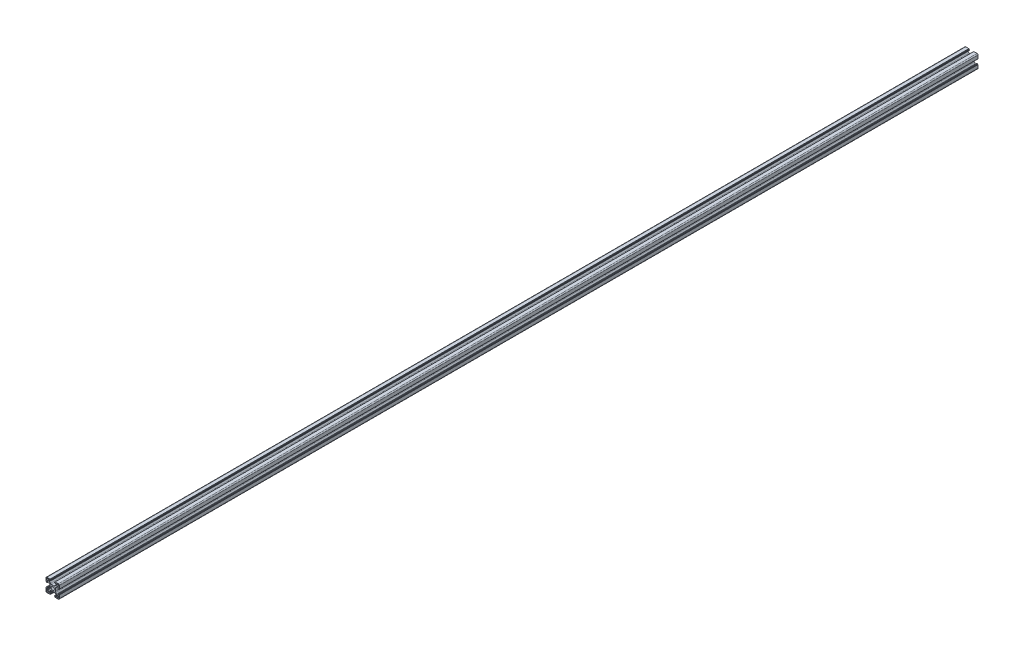
SolidWorks part; units mm, degrees
ref_plane "Спереди" through (0, 0, 0) normal (0, 0, 1) x (1, 0, 0)
ref_plane "Сверху" through (0, 0, 0) normal (0, 1, 0) x (1, 0, 0)
ref_plane "Справа" through (0, 0, 0) normal (1, 0, 0) x (0, 0, -1)
sketch "Эскиз1" plane through (0, 0, 0) normal (0, 0, 1) x (1, 0, 0)
  line L0 (-25.8933, 69.2728) -> (-28.8933, 66.2728) construction
  line L1 (-34.9933, 64.1728) -> (-33.0945, 64.1728)
  line L2 (-34.9933, 60.1728) -> (-24.9933, 70.1728) construction
  line L3 (-27.3933, 67.7728) -> (-28.8933, 69.2728) construction
  line L4 (-31.6803, 64.7586) -> (-30.3791, 66.0598)
  line L5 (-28.0933, 66.2728) -> (-26.6933, 66.2728)
  line L6 (-28.8933, 67.0728) -> (-28.8933, 68.4728)
  line L7 (-26.6933, 69.2728) -> (-28.0933, 69.2728)
  line L8 (-29.7933, 68.3728) -> (-29.7933, 67.474)
  line L9 (-31.2301, 68.246) -> (-30.7498, 68.7264)
  line L10 (-31.7933, 69.7219) -> (-31.2933, 69.7219)
  line L11 (-31.4069, 68.1728) -> (-31.6933, 68.1728)
  line L12 (-30.3962, 68.8728) -> (-30.2933, 68.8728)
  line L13 (-31.2933, 70.0228) -> (-31.2933, 69.7219)
  line L14 (-31.9433, 69.5719) -> (-31.9433, 68.4228)
  line L15 (-26.4933, 70.1728) -> (-31.1433, 70.1728)
  line L16 (-25.8933, 68.4728) -> (-25.8933, 67.0728)
  line L17 (-24.9933, 68.6728) -> (-24.9933, 64.0228)
  line L18 (-25.5943, 63.2228) -> (-26.7433, 63.2228)
  line L19 (-25.1433, 63.8728) -> (-25.4443, 63.8728)
  line L20 (-26.2933, 64.7699) -> (-26.2933, 64.8728)
  line L21 (-26.9933, 63.7592) -> (-26.9933, 63.4728)
  line L22 (-25.4443, 63.3728) -> (-25.4443, 63.8728)
  line L23 (-26.9201, 63.936) -> (-26.4398, 64.4164)
  line L24 (-26.7933, 65.3728) -> (-27.6921, 65.3728)
  line L25 (-30.4075, 63.4858) -> (-29.1063, 64.787)
  line L26 (-30.9933, 60.1728) -> (-30.9933, 62.0716)
  line L27 (-30.9933, 60.1728) -> (-30.9933, 58.274)
  line L28 (-30.4075, 56.8598) -> (-29.1063, 55.5586)
  line L29 (-28.8933, 53.2728) -> (-28.8933, 51.8728)
  line L30 (-28.0933, 54.0728) -> (-26.6933, 54.0728)
  line L31 (-25.8933, 51.8728) -> (-25.8933, 53.2728)
  line L32 (-26.7933, 54.9728) -> (-27.6921, 54.9728)
  line L33 (-26.9201, 56.4096) -> (-26.4398, 55.9292)
  line L34 (-25.4443, 56.9728) -> (-25.4443, 56.4728)
  line L35 (-26.9933, 56.5864) -> (-26.9933, 56.8728)
  line L36 (-26.2933, 55.5757) -> (-26.2933, 55.4728)
  line L37 (-25.1433, 56.4728) -> (-25.4443, 56.4728)
  line L38 (-25.5943, 57.1228) -> (-26.7433, 57.1228)
  line L39 (-24.9933, 51.6728) -> (-24.9933, 56.3228)
  line L40 (-26.6933, 51.0728) -> (-28.0933, 51.0728)
  line L41 (-26.4933, 50.1728) -> (-31.1433, 50.1728)
  line L42 (-31.9433, 50.7737) -> (-31.9433, 51.9228)
  line L43 (-31.2933, 50.3228) -> (-31.2933, 50.6237)
  line L44 (-30.3962, 51.4728) -> (-30.2933, 51.4728)
  line L45 (-31.4069, 52.1728) -> (-31.6933, 52.1728)
  line L46 (-31.7933, 50.6237) -> (-31.2933, 50.6237)
  line L47 (-31.2301, 52.0996) -> (-30.7498, 51.6192)
  line L48 (-29.7933, 51.9728) -> (-29.7933, 52.8716)
  line L49 (-31.6803, 55.587) -> (-30.3791, 54.2858)
  line L50 (-34.9933, 56.1728) -> (-33.0945, 56.1728)
  line L51 (-25.8933, 51.0728) -> (-28.8933, 54.0728) construction
  line L52 (-34.9933, 60.1728) -> (-24.9933, 50.1728) construction
  line L53 (-27.3933, 52.5728) -> (-25.8933, 54.0728) construction
  line L54 (-34.9933, 56.1728) -> (-36.8921, 56.1728)
  line L55 (-38.3063, 55.587) -> (-39.6075, 54.2858)
  line L56 (-41.8933, 54.0728) -> (-43.2933, 54.0728)
  line L57 (-41.0933, 53.2728) -> (-41.0933, 51.8728)
  line L58 (-43.2933, 51.0728) -> (-41.8933, 51.0728)
  line L59 (-40.1933, 51.9728) -> (-40.1933, 52.8716)
  line L60 (-38.7565, 52.0996) -> (-39.2369, 51.6192)
  line L61 (-38.1933, 50.6237) -> (-38.6933, 50.6237)
  line L62 (-38.5798, 52.1728) -> (-38.2933, 52.1728)
  line L63 (-39.5904, 51.4728) -> (-39.6933, 51.4728)
  line L64 (-38.6933, 50.3228) -> (-38.6933, 50.6237)
  line L65 (-38.0433, 50.7737) -> (-38.0433, 51.9228)
  line L66 (-43.4933, 50.1728) -> (-38.8433, 50.1728)
  line L67 (-44.0933, 51.8728) -> (-44.0933, 53.2728)
  line L68 (-44.9933, 51.6728) -> (-44.9933, 56.3228)
  line L69 (-44.3924, 57.1228) -> (-43.2433, 57.1228)
  line L70 (-44.8433, 56.4728) -> (-44.5424, 56.4728)
  line L71 (-43.6933, 55.5757) -> (-43.6933, 55.4728)
  line L72 (-42.9933, 56.5864) -> (-42.9933, 56.8728)
  line L73 (-44.5424, 56.9728) -> (-44.5424, 56.4728)
  line L74 (-43.0665, 56.4096) -> (-43.5469, 55.9292)
  line L75 (-43.1933, 54.9728) -> (-42.2945, 54.9728)
  line L76 (-39.5791, 56.8598) -> (-40.8803, 55.5586)
  line L77 (-38.9933, 60.1728) -> (-38.9933, 58.274)
  line L78 (-44.0933, 51.0728) -> (-41.0933, 54.0728) construction
  line L79 (-34.9933, 60.1728) -> (-44.9933, 50.1728) construction
  line L80 (-42.5933, 52.5728) -> (-41.0933, 51.0728) construction
  line L81 (-38.9933, 60.1728) -> (-38.9933, 62.0716)
  line L82 (-39.5791, 63.4858) -> (-40.8803, 64.787)
  line L83 (-41.0933, 67.0728) -> (-41.0933, 68.4728)
  line L84 (-41.8933, 66.2728) -> (-43.2933, 66.2728)
  line L85 (-44.0933, 68.4728) -> (-44.0933, 67.0728)
  line L86 (-43.1933, 65.3728) -> (-42.2945, 65.3728)
  line L87 (-43.0665, 63.936) -> (-43.5469, 64.4164)
  line L88 (-44.5424, 63.3728) -> (-44.5424, 63.8728)
  line L89 (-42.9933, 63.7592) -> (-42.9933, 63.4728)
  line L90 (-43.6933, 64.7699) -> (-43.6933, 64.8728)
  line L91 (-44.8433, 63.8728) -> (-44.5424, 63.8728)
  line L92 (-44.3924, 63.2228) -> (-43.2433, 63.2228)
  line L93 (-44.9933, 68.6728) -> (-44.9933, 64.0228)
  line L94 (-43.2933, 69.2728) -> (-41.8933, 69.2728)
  line L95 (-43.4933, 70.1728) -> (-38.8433, 70.1728)
  line L96 (-38.0433, 69.5719) -> (-38.0433, 68.4228)
  line L97 (-38.6933, 70.0228) -> (-38.6933, 69.7219)
  line L98 (-39.5904, 68.8728) -> (-39.6933, 68.8728)
  line L99 (-38.5798, 68.1728) -> (-38.2933, 68.1728)
  line L100 (-38.1933, 69.7219) -> (-38.6933, 69.7219)
  line L101 (-38.7565, 68.246) -> (-39.2369, 68.7264)
  line L102 (-40.1933, 68.3728) -> (-40.1933, 67.474)
  line L103 (-38.3063, 64.7586) -> (-39.6075, 66.0598)
  line L104 (-34.9933, 64.1728) -> (-36.8921, 64.1728)
  line L105 (-46.7574, 60.1728) -> (-23.489, 60.1728) construction
  line L106 (-44.0933, 69.2728) -> (-41.0933, 66.2728) construction
  line L107 (-34.9933, 48.0864) -> (-34.9933, 70.8917) construction
  line L108 (-34.9933, 60.1728) -> (-44.9933, 70.1728) construction
  line L109 (-42.5933, 67.7728) -> (-44.0933, 66.2728) construction
  arc A0 (-25.8933, 68.4728) -> (-26.6933, 69.2728) centre (-26.6933, 68.4728) ccw
  arc A1 (-28.0933, 69.2728) -> (-28.8933, 68.4728) centre (-28.0933, 68.4728) ccw
  arc A2 (-28.0933, 66.2728) -> (-28.8933, 67.0728) centre (-28.0933, 67.0728) cw
  arc A3 (-26.4933, 70.1728) -> (-24.9933, 68.6728) centre (-26.4933, 68.6728) cw
  arc A4 (-31.7933, 69.7219) -> (-31.9433, 69.5719) centre (-31.7933, 69.5719) ccw
  arc A5 (-31.1433, 70.1728) -> (-31.2933, 70.0228) centre (-31.1433, 70.0228) ccw
  arc A6 (-31.4069, 68.1728) -> (-31.2301, 68.246) centre (-31.4069, 68.4228) ccw
  arc A7 (-31.6933, 68.1728) -> (-31.9433, 68.4228) centre (-31.6933, 68.4228) cw
  arc A8 (-30.7498, 68.7264) -> (-30.3962, 68.8728) centre (-30.3962, 68.3728) cw
  arc A9 (-30.2933, 68.8728) -> (-29.7933, 68.3728) centre (-30.2933, 68.3728) cw
  arc A10 (-32.4933, 60.1728) -> (-34.9933, 62.6728) centre (-34.9933, 60.1728) ccw
  arc A11 (-33.0945, 64.1728) -> (-31.6803, 64.7586) centre (-33.0945, 66.1728) ccw
  arc A12 (-29.7933, 67.474) -> (-30.3791, 66.0598) centre (-31.7933, 67.474) cw
  arc A13 (-25.8933, 67.0728) -> (-26.6933, 66.2728) centre (-26.6933, 67.0728) cw
  arc A14 (-26.2933, 64.8728) -> (-26.7933, 65.3728) centre (-26.7933, 64.8728) ccw
  arc A15 (-26.4398, 64.4164) -> (-26.2933, 64.7699) centre (-26.7933, 64.7699) ccw
  arc A16 (-26.9933, 63.4728) -> (-26.7433, 63.2228) centre (-26.7433, 63.4728) ccw
  arc A17 (-26.9933, 63.7592) -> (-26.9201, 63.936) centre (-26.7433, 63.7592) cw
  arc A18 (-24.9933, 64.0228) -> (-25.1433, 63.8728) centre (-25.1433, 64.0228) cw
  arc A19 (-25.4443, 63.3728) -> (-25.5943, 63.2228) centre (-25.5943, 63.3728) cw
  arc A20 (-27.6921, 65.3728) -> (-29.1063, 64.787) centre (-27.6921, 63.3728) ccw
  arc A21 (-30.9933, 62.0716) -> (-30.4075, 63.4858) centre (-28.9933, 62.0716) cw
  arc A22 (-26.6933, 51.0728) -> (-25.8933, 51.8728) centre (-26.6933, 51.8728) ccw
  arc A23 (-25.8933, 53.2728) -> (-26.6933, 54.0728) centre (-26.6933, 53.2728) ccw
  arc A24 (-28.8933, 53.2728) -> (-28.0933, 54.0728) centre (-28.0933, 53.2728) cw
  arc A25 (-24.9933, 51.6728) -> (-26.4933, 50.1728) centre (-26.4933, 51.6728) cw
  arc A26 (-25.4443, 56.9728) -> (-25.5943, 57.1228) centre (-25.5943, 56.9728) ccw
  arc A27 (-24.9933, 56.3228) -> (-25.1433, 56.4728) centre (-25.1433, 56.3228) ccw
  arc A28 (-26.9933, 56.5864) -> (-26.9201, 56.4096) centre (-26.7433, 56.5864) ccw
  arc A29 (-26.9933, 56.8728) -> (-26.7433, 57.1228) centre (-26.7433, 56.8728) cw
  arc A30 (-26.4398, 55.9292) -> (-26.2933, 55.5757) centre (-26.7933, 55.5757) cw
  arc A31 (-26.2933, 55.4728) -> (-26.7933, 54.9728) centre (-26.7933, 55.4728) cw
  arc A32 (-34.9933, 57.6728) -> (-32.4933, 60.1728) centre (-34.9933, 60.1728) ccw
  arc A33 (-30.9933, 58.274) -> (-30.4075, 56.8598) centre (-28.9933, 58.274) ccw
  arc A34 (-27.6921, 54.9728) -> (-29.1063, 55.5586) centre (-27.6921, 56.9728) cw
  arc A35 (-28.0933, 51.0728) -> (-28.8933, 51.8728) centre (-28.0933, 51.8728) cw
  arc A36 (-30.2933, 51.4728) -> (-29.7933, 51.9728) centre (-30.2933, 51.9728) ccw
  arc A37 (-30.7498, 51.6192) -> (-30.3962, 51.4728) centre (-30.3962, 51.9728) ccw
  arc A38 (-31.6933, 52.1728) -> (-31.9433, 51.9228) centre (-31.6933, 51.9228) ccw
  arc A39 (-31.4069, 52.1728) -> (-31.2301, 52.0996) centre (-31.4069, 51.9228) cw
  arc A40 (-31.1433, 50.1728) -> (-31.2933, 50.3228) centre (-31.1433, 50.3228) cw
  arc A41 (-31.7933, 50.6237) -> (-31.9433, 50.7737) centre (-31.7933, 50.7737) cw
  arc A42 (-29.7933, 52.8716) -> (-30.3791, 54.2858) centre (-31.7933, 52.8716) ccw
  arc A43 (-33.0945, 56.1728) -> (-31.6803, 55.587) centre (-33.0945, 54.1728) cw
  arc A44 (-44.0933, 51.8728) -> (-43.2933, 51.0728) centre (-43.2933, 51.8728) ccw
  arc A45 (-41.8933, 51.0728) -> (-41.0933, 51.8728) centre (-41.8933, 51.8728) ccw
  arc A46 (-41.8933, 54.0728) -> (-41.0933, 53.2728) centre (-41.8933, 53.2728) cw
  arc A47 (-43.4933, 50.1728) -> (-44.9933, 51.6728) centre (-43.4933, 51.6728) cw
  arc A48 (-38.1933, 50.6237) -> (-38.0433, 50.7737) centre (-38.1933, 50.7737) ccw
  arc A49 (-38.8433, 50.1728) -> (-38.6933, 50.3228) centre (-38.8433, 50.3228) ccw
  arc A50 (-38.5798, 52.1728) -> (-38.7565, 52.0996) centre (-38.5798, 51.9228) ccw
  arc A51 (-38.2933, 52.1728) -> (-38.0433, 51.9228) centre (-38.2933, 51.9228) cw
  arc A52 (-39.2369, 51.6192) -> (-39.5904, 51.4728) centre (-39.5904, 51.9728) cw
  arc A53 (-39.6933, 51.4728) -> (-40.1933, 51.9728) centre (-39.6933, 51.9728) cw
  arc A54 (-37.4933, 60.1728) -> (-34.9933, 57.6728) centre (-34.9933, 60.1728) ccw
  arc A55 (-36.8921, 56.1728) -> (-38.3063, 55.587) centre (-36.8921, 54.1728) ccw
  arc A56 (-40.1933, 52.8716) -> (-39.6075, 54.2858) centre (-38.1933, 52.8716) cw
  arc A57 (-44.0933, 53.2728) -> (-43.2933, 54.0728) centre (-43.2933, 53.2728) cw
  arc A58 (-43.6933, 55.4728) -> (-43.1933, 54.9728) centre (-43.1933, 55.4728) ccw
  arc A59 (-43.5469, 55.9292) -> (-43.6933, 55.5757) centre (-43.1933, 55.5757) ccw
  arc A60 (-42.9933, 56.8728) -> (-43.2433, 57.1228) centre (-43.2433, 56.8728) ccw
  arc A61 (-42.9933, 56.5864) -> (-43.0665, 56.4096) centre (-43.2433, 56.5864) cw
  arc A62 (-44.9933, 56.3228) -> (-44.8433, 56.4728) centre (-44.8433, 56.3228) cw
  arc A63 (-44.5424, 56.9728) -> (-44.3924, 57.1228) centre (-44.3924, 56.9728) cw
  arc A64 (-42.2945, 54.9728) -> (-40.8803, 55.5586) centre (-42.2945, 56.9728) ccw
  arc A65 (-38.9933, 58.274) -> (-39.5791, 56.8598) centre (-40.9933, 58.274) cw
  arc A66 (-43.2933, 69.2728) -> (-44.0933, 68.4728) centre (-43.2933, 68.4728) ccw
  arc A67 (-44.0933, 67.0728) -> (-43.2933, 66.2728) centre (-43.2933, 67.0728) ccw
  arc A68 (-41.0933, 67.0728) -> (-41.8933, 66.2728) centre (-41.8933, 67.0728) cw
  arc A69 (-44.9933, 68.6728) -> (-43.4933, 70.1728) centre (-43.4933, 68.6728) cw
  arc A70 (-44.5424, 63.3728) -> (-44.3924, 63.2228) centre (-44.3924, 63.3728) ccw
  arc A71 (-44.9933, 64.0228) -> (-44.8433, 63.8728) centre (-44.8433, 64.0228) ccw
  arc A72 (-42.9933, 63.7592) -> (-43.0665, 63.936) centre (-43.2433, 63.7592) ccw
  arc A73 (-42.9933, 63.4728) -> (-43.2433, 63.2228) centre (-43.2433, 63.4728) cw
  arc A74 (-43.5469, 64.4164) -> (-43.6933, 64.7699) centre (-43.1933, 64.7699) cw
  arc A75 (-43.6933, 64.8728) -> (-43.1933, 65.3728) centre (-43.1933, 64.8728) cw
  arc A76 (-34.9933, 62.6728) -> (-37.4933, 60.1728) centre (-34.9933, 60.1728) ccw
  arc A77 (-38.9933, 62.0716) -> (-39.5791, 63.4858) centre (-40.9933, 62.0716) ccw
  arc A78 (-42.2945, 65.3728) -> (-40.8803, 64.787) centre (-42.2945, 63.3728) cw
  arc A79 (-41.8933, 69.2728) -> (-41.0933, 68.4728) centre (-41.8933, 68.4728) cw
  arc A80 (-39.6933, 68.8728) -> (-40.1933, 68.3728) centre (-39.6933, 68.3728) ccw
  arc A81 (-39.2369, 68.7264) -> (-39.5904, 68.8728) centre (-39.5904, 68.3728) ccw
  arc A82 (-38.2933, 68.1728) -> (-38.0433, 68.4228) centre (-38.2933, 68.4228) ccw
  arc A83 (-38.5798, 68.1728) -> (-38.7565, 68.246) centre (-38.5798, 68.4228) cw
  arc A84 (-38.8433, 70.1728) -> (-38.6933, 70.0228) centre (-38.8433, 70.0228) cw
  arc A85 (-38.1933, 69.7219) -> (-38.0433, 69.5719) centre (-38.1933, 69.5719) cw
  arc A86 (-40.1933, 67.474) -> (-39.6075, 66.0598) centre (-38.1933, 67.474) ccw
  arc A87 (-36.8921, 64.1728) -> (-38.3063, 64.7586) centre (-36.8921, 66.1728) cw
  point P0 (-34.9933, 60.1728)
  point P9 (-34.9933, 60.1728)
  point P40 (-26.2933, 63.8728)
  point P93 (-31.2933, 51.4728)
  point P144 (-31.2933, 68.8728)
  point P152 (-26.2933, 56.4728)
  point P153 (-34.9933, 56.2485)
  point P154 (-34.9933, 60.1728)
  point P189 (-43.6933, 56.4728)
  point P228 (-38.6933, 51.4728)
  point P229 (-38.9176, 60.1728)
  point P230 (-34.9933, 60.1728)
  point P268 (-38.6933, 68.8728)
  point P273 (-31.0691, 60.1728)
  point P306 (-43.6933, 63.8728)
  point P307 (-34.9933, 64.0971)
  point P309 (-34.9933, 60.1728)
  dimension "D3" = 5
  dimension "D6" = 2
  dimension "D1" = 2
  dimension "D2" = 6
  dimension "D4" = 4
  dimension "D5" = 0.9
extrude "Бобышка-Вытянуть1" add sketch "Эскиз1" along normal blind 1380
